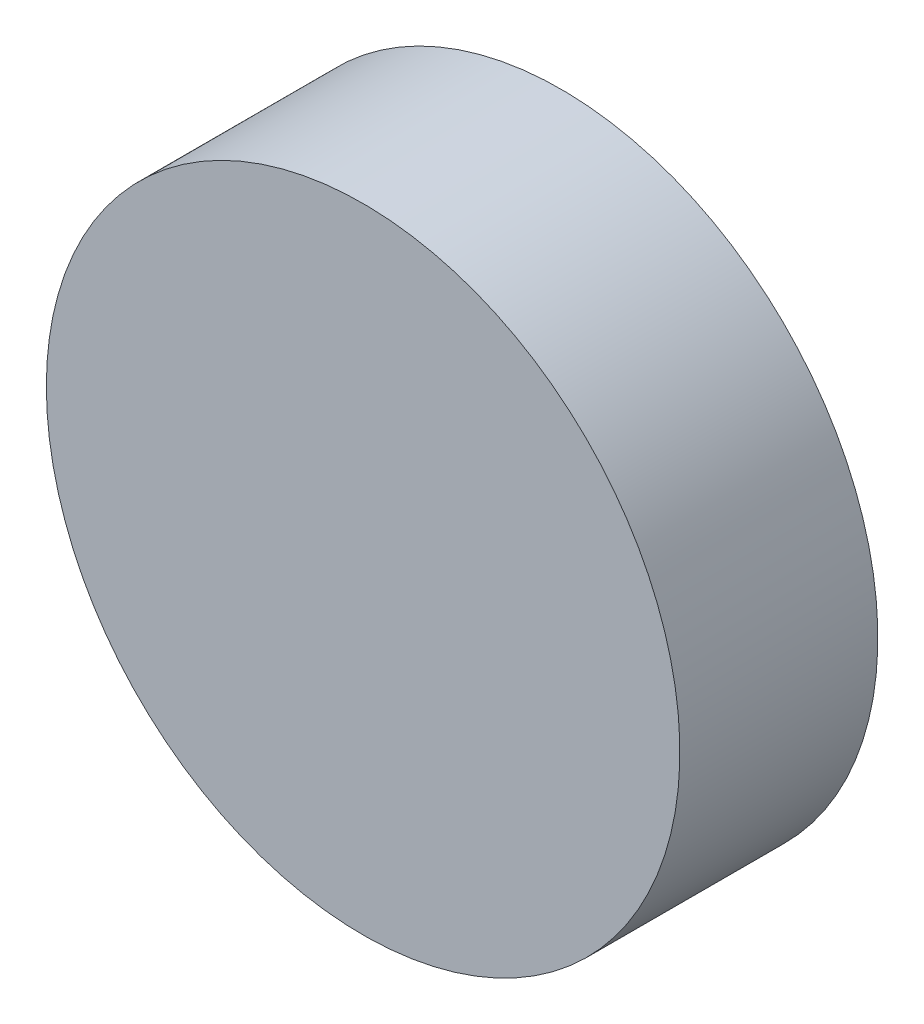
SolidWorks part; units mm, degrees
material "PET"
ref_plane "Спереди" through (0, 0, 0) normal (0, 0, 1) x (1, 0, 0)
ref_plane "Сверху" through (0, 0, 0) normal (0, 1, 0) x (1, 0, 0)
ref_plane "Справа" through (0, 0, 0) normal (1, 0, 0) x (0, 0, -1)
sketch "Эскиз1" plane through (0, 0, 0) normal (0, 1, 0) x (1, 0, 0)
  line L0 (0, 0) -> (8, 0)
  line L1 (8, 0) -> (8, 5)
  line L2 (8, 5) -> (3, 5)
  line L3 (3, 5) -> (3, 6)
  line L4 (3, 6) -> (2, 6)
  line L5 (2, 6) -> (2, 9)
  line L6 (2, 9) -> (0, 9)
  line L7 (0, 9) -> (0, 0)
  dimension "D1" = 8
  dimension "D2" = 5
  dimension "D3" = 1
  dimension "D4" = 3
  dimension "D5" = 2
  dimension "D6" = 1
revolve "База" add sketch "Эскиз1" angle 360 about L7
chamfer "Фаска1" distance 0.5 angle 45 1 edges at (-2, 0, -9)
